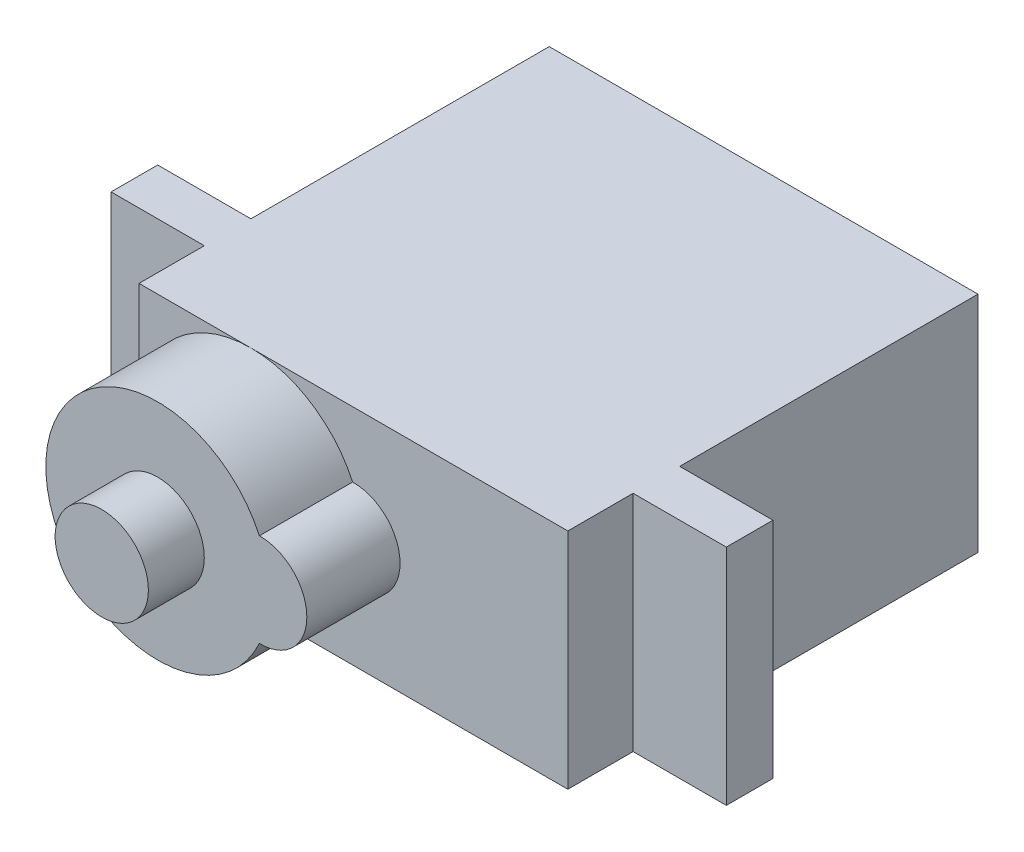
SolidWorks part; units mm, degrees
ref_plane "Plan de face" through (0, 0, 0) normal (0, 0, 1) x (1, 0, 0)
ref_plane "Plan de dessus" through (0, 0, 0) normal (0, 1, 0) x (1, 0, 0)
ref_plane "Plan de droite" through (0, 0, 0) normal (1, 0, 0) x (0, 0, -1)
sketch "Esquisse1" plane through (0, 0, 0) normal (0, 0, 1) x (1, 0, 0)
  line L1 (-11.5, -6) -> (11.5, -6)
  line L2 (-11.5, -6) -> (-11.5, 6)
  line L3 (-11.5, 6) -> (11.5, 6)
  line L4 (11.5, -6) -> (11.5, 6)
  line L5 (-11.5, -6) -> (11.5, 6) construction
  line L6 (-11.5, 6) -> (11.5, -6) construction
  point P0 (0, 0)
  dimension "D1" = 23
  dimension "D2" = 12
extrude "Boss.-Extru.1" add sketch "Esquisse1" along normal blind 22
sketch "Esquisse2" plane through (0, 0, 22) normal (0, 0, 1) x (1, 0, 0)
  circle A0 centre (0, 0) radius 2.5
  circle A1 centre (-5.5, 0) radius 6
  dimension "D1" = 5
extrude "Boss.-Extru.2" add sketch "Esquisse2" along normal blind 5 contours A0 A1 | A0 A1 | A1 A0
sketch "Esquisse3" plane through (0, 0, 27) normal (0, 0, 1) x (1, 0, 0)
  circle A0 centre (-5.5, 0) radius 6
  circle A1 centre (-5.5, 0) radius 2.5
  dimension "D1" = 5
extrude "Boss.-Extru.3" add sketch "Esquisse3" along normal blind 3 contours A1
sketch "Esquisse4" plane through (-11.5, 0, 0) normal (-1, 0, 0) x (0, 0, 1)
  line L0 (22, 6) -> (0, 6) construction
  line L1 (18.5, 6) -> (16, 6)
  line L2 (18.5, 6) -> (18.5, -6)
  line L3 (18.5, -6) -> (16, -6)
  line L4 (16, 6) -> (16, -6)
  line L5 (22, -6) -> (0, -6) construction
  line L6 (0, 6) -> (0, -6) construction
  dimension "D1" = 16
  dimension "D2" = 2.5
extrude "Boss.-Extru.4" add sketch "Esquisse4" along normal blind 5
mirror "Symétrie1" about plane through (0, 0, 0) normal (1, 0, 0) of "Boss.-Extru.4"
